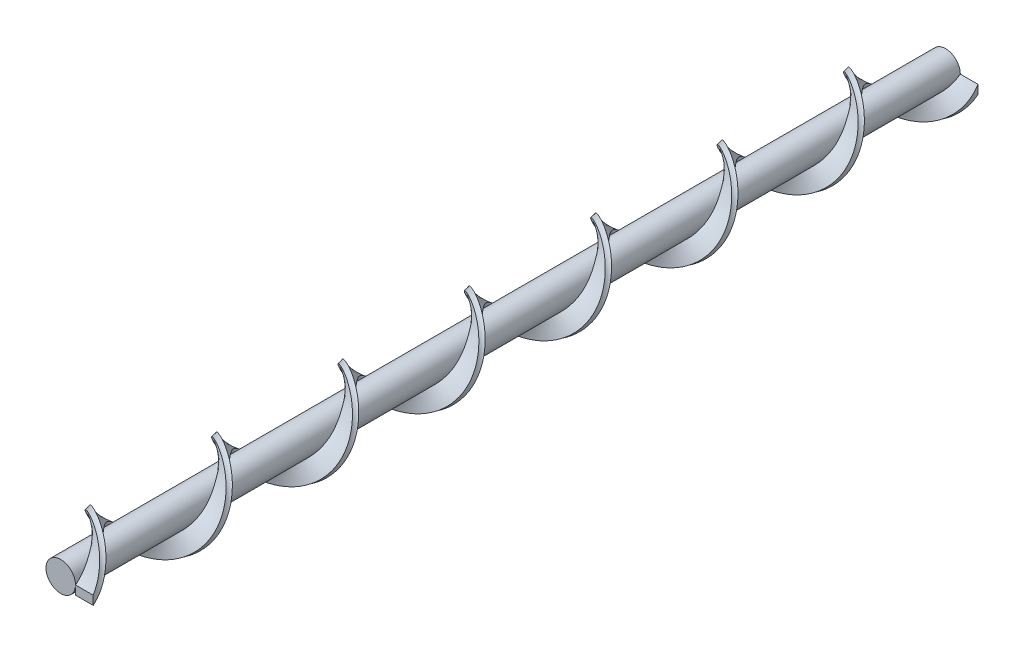
SolidWorks part; units mm, degrees
material "6061-T6 (SS)"
ref_plane "Front Plane" through (0, 0, 0) normal (0, 0, 1) x (1, 0, 0)
ref_plane "Top Plane" through (0, 0, 0) normal (0, 1, 0) x (1, 0, 0)
ref_plane "Right Plane" through (0, 0, 0) normal (1, 0, 0) x (0, 0, -1)
sketch "Sketch1" plane through (0, 0, 0) normal (0, 0, 1) x (1, 0, 0)
  circle A0 centre (0, 0) radius 2.5
  dimension "D1" = 5
extrude "Boss-Extrude1" add sketch "Sketch1" along normal blind 150
sketch "Sketch3" plane through (0, 0, 150) normal (0, 0, 1) x (1, 0, 0)
  circle A0 centre (0, 0) radius 2.5
sketch "Sketch11" plane through (0, 0, 0) normal (0, 0, -1) x (-1, 0, 0)
  circle A0 centre (0, 0) radius 2.5
curve "Helix/Spiral3" pitch 21.4286 height 150 turns 7
ref_plane "Plane3" through (0, 0, 0) normal (0, 0, -1) x (-1, 0, 0)
sketch "Sketch12" plane through (0, 0, 0) normal (0, 0, -1) x (-1, 0, 0)
  line L1 (-2.5, 0) -> (-5.5, 0)
  line L2 (-2.5, 0) -> (-2.5, -1.5)
  line L3 (-2.5, -1.5) -> (-5.5, -1.5)
  line L4 (-5.5, 0) -> (-5.5, -1.5)
  circle A0 centre (0, 0) radius 2.5 construction
  dimension "D1" = 1.5
  dimension "D2" = 3
sweep "Sweep5" add profiles "Sketch12" path "Helix/Spiral3"
